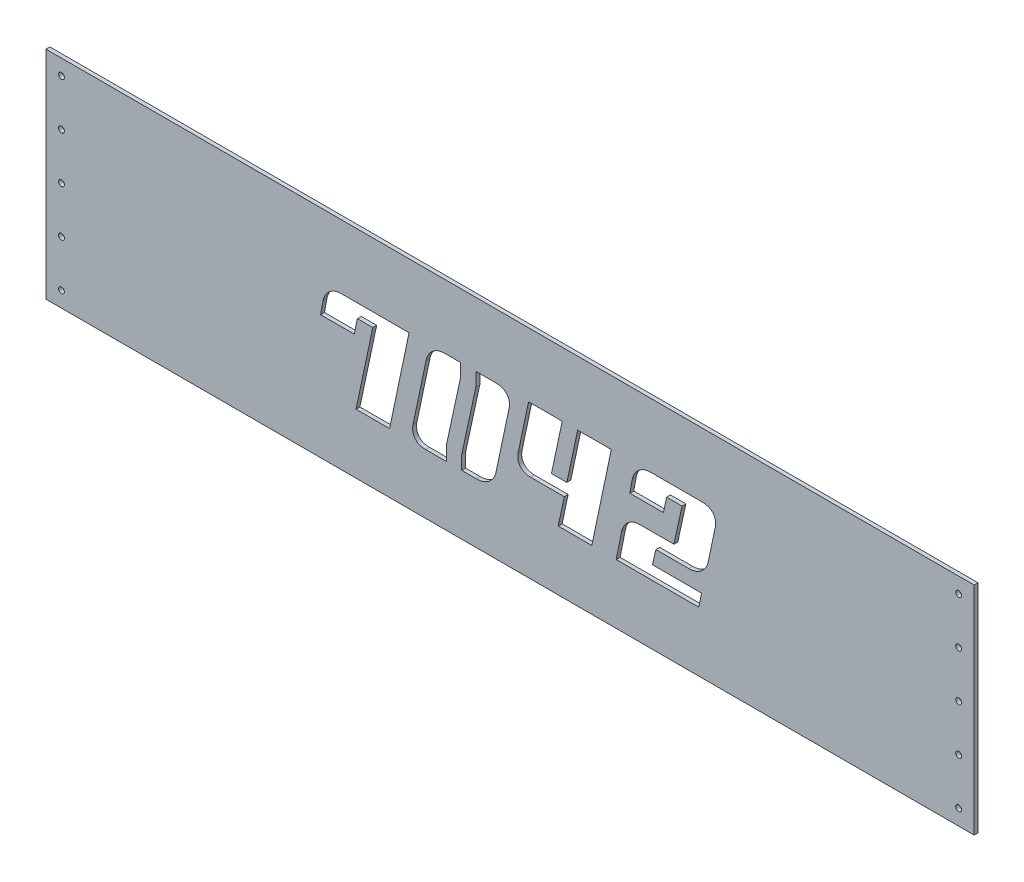
SolidWorks part; units mm, degrees
ref_plane "Front Plane" through (0, 0, 0) normal (0, 0, 1) x (1, 0, 0)
ref_plane "Top Plane" through (0, 0, 0) normal (0, 1, 0) x (1, 0, 0)
ref_plane "Right Plane" through (0, 0, 0) normal (1, 0, 0) x (0, 0, -1)
sketch "Sketch1" plane through (0, 0, 0) normal (0, 0, 1) x (1, 0, 0)
  line L0 (-381, -39.9147) -> (381, -39.9147) construction
  line L1 (-381, 88.9) -> (381, 88.9)
  line L2 (-381, 88.9) -> (-381, -88.9)
  line L3 (-381, -88.9) -> (381, -88.9)
  line L4 (381, 88.9) -> (381, -88.9)
  line L5 (-381, 88.9) -> (381, -88.9) construction
  line L6 (-381, -88.9) -> (381, 88.9) construction
  line L7 (-98.8981, -39.8353) -> (-126.473, -39.8353)
  line L8 (-126.473, -39.8353) -> (-112.6935, 25.1093)
  line L9 (-112.6935, 25.1093) -> (-125.3935, 25.1093)
  line L10 (-125.3935, 25.1093) -> (-127.9811, 12.8221)
  line L11 (-127.9811, 12.8221) -> (-155.556, 12.8221)
  line L12 (-155.556, 12.8221) -> (-153.4922, 24.0616)
  line L13 (-138.3792, 36.2853) -> (-82.9437, 36.2853)
  line L14 (-82.9437, 36.2853) -> (-98.8981, -39.8353)
  line L15 (-27.6955, -39.9147) -> (-69.4785, -39.9147)
  line L16 (-79.6227, -27.0877) -> (-68.8594, 23.8711)
  line L17 (-53.7464, 36.2853) -> (-11.9634, 36.2853)
  line L18 (-0.8509, 23.4424) -> (-11.6142, -27.5322)
  line L19 (-40.7607, 25.1093) -> (-52.3653, -28.7387)
  line L20 (-52.3653, -28.7387) -> (-39.7129, -28.7387)
  line L21 (-39.7129, -28.7387) -> (-28.0606, 25.1093)
  line L22 (-28.0606, 25.1093) -> (-40.7607, 25.1093)
  line L23 (42.8244, 36.2853) -> (33.982, -5.3707)
  line L24 (33.982, -5.3707) -> (46.6344, -5.3707)
  line L25 (46.6344, -5.3707) -> (55.4768, 36.2853)
  line L26 (55.4768, 36.2853) -> (83.0993, 36.2853)
  line L27 (83.0993, 36.2853) -> (67.129, -39.9147)
  line L28 (67.129, -39.9147) -> (39.5541, -39.9147)
  line L29 (39.5541, -39.9147) -> (44.5071, -16.5467)
  line L30 (44.5071, -16.5467) -> (16.8846, -16.5467)
  line L31 (6.7246, -3.7514) -> (15.186, 36.2853)
  line L32 (15.186, 36.2853) -> (42.8244, 36.2853)
  line L33 (116.9003, -28.7387) -> (157.1752, -28.7387)
  line L34 (157.1752, -28.7387) -> (155.0003, -39.9147)
  line L35 (155.0003, -39.9147) -> (87.1347, -39.9147)
  line L36 (87.1347, -39.9147) -> (91.5797, -17.8008)
  line L37 (106.6768, -5.3707) -> (134.5057, -5.3707)
  line L38 (134.5057, -5.3707) -> (141.205, 25.1093)
  line L39 (141.205, 25.1093) -> (128.505, 25.1093)
  line L40 (128.505, 25.1093) -> (125.9173, 12.8221)
  line L41 (125.9173, 12.8221) -> (98.3425, 12.8221)
  line L42 (98.3425, 12.8221) -> (100.4062, 24.0616)
  line L43 (115.5192, 36.2853) -> (157.3022, 36.2853)
  line L44 (168.4147, 23.4742) -> (162.6045, -4.1959)
  line L45 (146.5231, -16.5467) -> (119.6785, -16.5467)
  line L46 (119.6785, -16.5467) -> (116.9003, -28.7387)
  spline S0 degree 3 poles (-153.4922, 24.0616) (-153.114, 25.8268) (-152.1071, 28.3309) (-150.0188, 31.2087) (-148.1105, 33.0002) (-145.9524, 34.4742) (-142.7564, 35.8998) (-140.1317, 36.2924) (-138.3792, 36.2853) knots 0 0 0 0 0.256781 0.37927 0.504103 0.627939 0.750156 1 1 1 1
  spline S1 degree 3 poles (-11.6142, -27.5322) (-11.9877, -29.2406) (-13.0111, -31.7054) (-15.1535, -34.5415) (-16.7945, -36.1129) (-18.2855, -37.1933) (-19.4537, -37.9343) (-20.6945, -38.5338) (-21.9777, -39.0547) (-23.3348, -39.4205) (-25.2294, -39.8266) (-26.7054, -39.8905) (-27.6955, -39.9147) knots 0 0 0 0 0.238595 0.358933 0.483744 0.547388 0.610401 0.672498 0.735481 0.799355 0.864312 1 1 1 1
  spline S2 degree 3 poles (-69.4785, -39.9147) (-70.3784, -39.8907) (-71.7049, -39.8342) (-73.3673, -39.4281) (-74.4978, -39.0545) (-75.5231, -38.5442) (-76.4675, -37.9335) (-77.3034, -37.1992) (-78.0554, -36.3728) (-78.6945, -35.4506) (-79.1921, -34.4448) (-79.6096, -33.3882) (-79.8461, -32.2508) (-80.0027, -31.0506) (-79.9798, -29.3103) (-79.8192, -27.9811) (-79.6226, -27.0877) knots 0 0 0 0 0.140211 0.204364 0.265148 0.324658 0.381614 0.439258 0.496832 0.554704 0.612745 0.670716 0.730498 0.792545 0.858256 1 1 1 1
  spline S3 degree 3 poles (-68.8594, 23.8711) (-68.4628, 25.6431) (-67.5054, 28.2067) (-65.3845, 31.1011) (-63.4957, 32.9404) (-61.3401, 34.4425) (-58.1378, 35.8891) (-55.5064, 36.2991) (-53.7464, 36.2853) knots 0 0 0 0 0.257514 0.38084 0.505341 0.629199 0.75091 1 1 1 1
  spline S4 degree 3 poles (-11.9634, 36.2853) (-10.9512, 36.2651) (-9.472, 36.1989) (-7.5986, 35.8096) (-6.362, 35.3939) (-5.227, 34.8843) (-4.2094, 34.2522) (-3.3095, 33.4904) (-2.5178, 32.6391) (-1.8493, 31.6976) (-1.3055, 30.69) (-0.8889, 29.6248) (-0.6187, 28.4922) (-0.4797, 27.3095) (-0.4618, 25.6064) (-0.6404, 24.311) (-0.8509, 23.4424) knots 0 0 0 0 0.150989 0.21945 0.284234 0.344881 0.404348 0.461955 0.519943 0.577008 0.633416 0.690045 0.746804 0.806324 0.867001 1 1 1 1
  spline S5 degree 3 poles (16.8846, -16.5467) (15.974, -16.5668) (14.6545, -16.4428) (12.9697, -16.0842) (11.8485, -15.6853) (10.8145, -15.1872) (9.866, -14.5858) (9.0286, -13.8465) (8.2748, -13.0213) (7.6437, -12.1005) (7.1267, -11.1052) (6.7492, -10.0407) (6.4968, -8.9106) (6.3457, -7.714) (6.3667, -5.9743) (6.5285, -4.6447) (6.7246, -3.7514) knots 0 0 0 0 0.141056 0.205006 0.266817 0.325212 0.382839 0.440467 0.498024 0.555879 0.613172 0.671613 0.730576 0.792605 0.858298 1 1 1 1
  spline S6 degree 3 poles (91.5797, -17.8008) (91.9707, -16.025) (92.9431, -13.4754) (95.0378, -10.5622) (96.6267, -9.0308) (98.0413, -7.9846) (99.14, -7.2708) (100.2983, -6.6892) (101.4958, -6.2139) (102.7242, -5.8247) (104.4467, -5.4626) (105.779, -5.3648) (106.6768, -5.3707) knots 0 0 0 0 0.257512 0.380397 0.505435 0.568066 0.629375 0.690689 0.751205 0.811629 0.872901 1 1 1 1
  spline S7 degree 3 poles (100.4062, 24.0616) (100.7844, 25.8268) (101.7913, 28.3309) (103.8796, 31.2087) (105.7879, 33.0002) (107.946, 34.4742) (111.142, 35.8998) (113.7667, 36.2924) (115.5192, 36.2853) knots 0 0 0 0 0.256781 0.37927 0.504103 0.627939 0.750156 1 1 1 1
  spline S8 degree 3 poles (157.3022, 36.2853) (158.3134, 36.2623) (159.7954, 36.2039) (161.663, 35.8033) (162.9153, 35.4156) (164.0416, 34.8809) (165.0773, 34.2714) (165.9711, 33.5049) (166.7641, 32.6555) (167.4313, 31.713) (167.9758, 30.7131) (168.3785, 29.6442) (168.6439, 28.5182) (168.7871, 27.3361) (168.803, 25.638) (168.6256, 24.3428) (168.4147, 23.4742) knots 0 0 0 0 0.151087 0.219592 0.284173 0.345905 0.404997 0.462641 0.520667 0.577769 0.634214 0.68986 0.747423 0.806199 0.866915 1 1 1 1
  spline S9 degree 3 poles (162.6045, -4.1959) (162.2228, -5.8954) (161.2127, -8.3578) (159.0605, -11.1761) (157.4236, -12.737) (155.947, -13.8296) (154.7773, -14.5702) (153.5275, -15.1622) (152.2455, -15.6838) (150.8903, -16.0574) (148.9934, -16.454) (147.5137, -16.5248) (146.5231, -16.5467) knots 0 0 0 0 0.238188 0.358091 0.48305 0.546188 0.609275 0.672095 0.735154 0.798407 0.864151 1 1 1 1
  point P0 (0, 0)
  dimension "D1" = 762
  dimension "D2" = 177.8
extrude "Boss-Extrude1" add sketch "Sketch1" along normal blind 3.175 contours L4 L1 L2 L3 | L21 L22 L19 L20
sketch "Sketch2" plane through (0, 0, 3.175) normal (0, 0, 1) x (1, 0, 0)
  line L1 (-28.0606, 25.1093) -> (-40.7606, 25.1093)
  line L2 (-28.0606, 25.1093) -> (-28.0606, 50.3078)
  line L3 (-28.0606, 50.3078) -> (-40.7606, 50.3078)
  line L4 (-40.7606, 25.1093) -> (-40.7606, 50.3078)
  line L5 (-52.3653, -28.7387) -> (-39.7129, -28.7387)
  line L6 (-52.3653, -28.7387) -> (-52.3653, -49.6221)
  line L7 (-52.3653, -49.6221) -> (-39.7129, -49.6221)
  line L8 (-39.7129, -28.7387) -> (-39.7129, -49.6221)
extrude "Boss-Extrude2" add sketch "Sketch2" against normal blind 3.175
sketch "Sketch3" plane through (0, 0, 3.175) normal (0, 0, 1) x (1, 0, 0)
  line L0 (0, 88.9) -> (0, -88.9) construction
  line L1 (-381, 88.9) -> (381, 88.9) construction
  line L2 (-381, -88.9) -> (381, -88.9) construction
  line L3 (-381, 0) -> (381, 0) construction
  line L4 (-381, 88.9) -> (-381, -88.9) construction
  line L5 (381, 88.9) -> (381, -88.9) construction
  circle A0 centre (-368.3, 76.2) radius 2.413
  circle A3 centre (-368.3, 38.1) radius 2.413
  circle A4 centre (-368.3, 0) radius 2.413
  circle A5 centre (-368.3, -38.1) radius 2.413
  circle A6 centre (-368.3, -76.2) radius 2.413
  circle A7 centre (368.3, -76.2) radius 2.413
  circle A8 centre (368.3, -38.1) radius 2.413
  circle A9 centre (368.3, 0) radius 2.413
  circle A10 centre (368.3, 38.1) radius 2.413
  circle A11 centre (368.3, 76.2) radius 2.413
  dimension "D3" = 4.826
  dimension "D1" = 12.7
  dimension "D2" = 12.7
  dimension "D4" = 5
extrude "Cut-Extrude1" cut sketch "Sketch3" against normal through all
